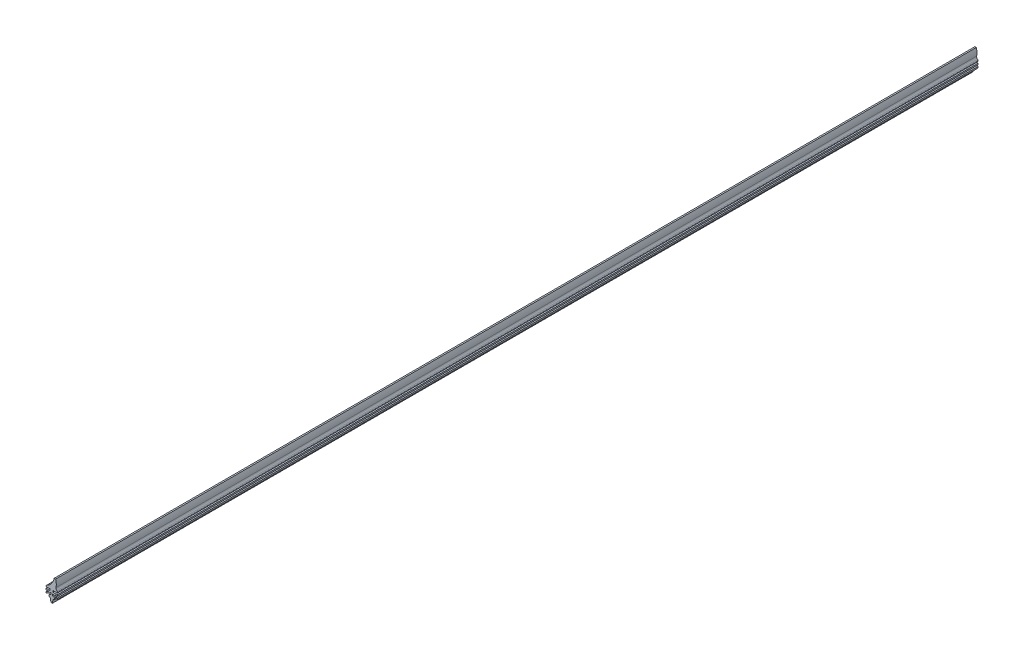
SolidWorks part; units mm, degrees
material "Caoutchouc"
ref_plane "Plan de face" through (0, 0, 0) normal (0, 0, 1) x (1, 0, 0)
ref_plane "Plan de dessus" through (0, 0, 0) normal (0, 1, 0) x (1, 0, 0)
ref_plane "Plan de droite" through (0, 0, 0) normal (1, 0, 0) x (0, 0, -1)
sketch "Esquisse1" plane through (0, 0, 0) normal (0, 0, 1) x (1, 0, 0)
  line L0 (0, 0) -> (0, -7.2441) construction
  line L1 (4, 0) -> (1, 0)
  line L2 (-8, 0) -> (-1, 0) construction
  line L3 (-4, 0) -> (-4, -1)
  line L4 (4, 0) -> (4, -1)
  line L5 (-4, -1) -> (-2.2647, -1)
  line L6 (4, -1) -> (2.2647, -1)
  line L7 (-2.2647, -1) -> (-4, -2)
  line L8 (2.2647, -1) -> (4, -2)
  line L9 (-4, -2) -> (-4, -3)
  line L10 (4, -2) -> (4, -3)
  line L11 (-4, -3) -> (-0.5, -0.9831)
  line L12 (4, -3) -> (0.5, -0.9831)
  line L13 (-0.5, -0.9831) -> (-0.5, -2.1372)
  line L14 (0.5, -0.9831) -> (0.5, -2.1372)
  line L15 (-0.5, -2.1372) -> (-2, -3.0016)
  line L16 (0.5, -2.1372) -> (2, -3.0016)
  line L17 (-2, -3.0016) -> (-2, -4.0016)
  line L18 (2, -3.0016) -> (2, -4.0016)
  line L19 (-2, -4.0016) -> (-1.8471, -4.0016)
  line L20 (2, -4.0016) -> (1.8471, -4.0016)
  line L21 (-0.8607, -4.8371) -> (-0.5, -7)
  line L22 (0.8607, -4.8371) -> (0.5, -7)
  line L23 (-0.5, -7) -> (0.5, -7)
  line L24 (1, 1) -> (8, 1) construction
  line L25 (0, 0) -> (0, 8.6585) construction
  line L26 (8, 1) -> (8, 0) construction
  line L27 (-8, 1) -> (-1, 1) construction
  line L28 (1.798, 9) -> (2.798, 9)
  line L29 (4, 1.5) -> (4, 1)
  line L30 (-4, 1.202) -> (-4, 1)
  line L31 (-8, 1) -> (-8, 0) construction
  line L32 (-1, 1) -> (-4, 1)
  line L33 (-1, 1) -> (-1, 0)
  line L34 (1, 0) -> (1, 1)
  line L35 (1, 1) -> (4, 1)
  line L36 (-1, 0) -> (-4, 0)
  arc A0 (0.8607, -4.8371) -> (1.8471, -4.0016) centre (1.8471, -5.0016) cw
  arc A1 (-0.8607, -4.8371) -> (-1.8471, -4.0016) centre (-1.8471, -5.0016) ccw
  arc A2 (-3.4545, 2.0928) -> (1.798, 9) centre (-8, 11) ccw
  arc A3 (3.035, 3.8221) -> (3.6, 2.3) centre (4.5, 3.5) ccw
  arc A4 (-4, 1.202) -> (-3.4545, 2.0928) centre (-3, 1.202) cw
  arc A5 (3.035, 3.8221) -> (2.798, 9) centre (-6.7317, 5.9694) ccw
  arc A6 (4, 1.5) -> (3.6, 2.3) centre (3, 1.5) ccw
  point P28 (0, -7)
  point P32 (1, -4.0016)
  point P35 (-1, -4.0016)
  dimension "D13" = 1
  dimension "D16" = 20
  dimension "D19" = 3
  dimension "D22" = 1
  dimension "D1" = 1
  dimension "D2" = 4
  dimension "D3" = 1
  dimension "D4" = 8
  dimension "D5" = 8
  dimension "D6" = 1
  dimension "D7" = 1
  dimension "D8" = 1
  dimension "D9" = 1
  dimension "D10" = 1
  dimension "D11" = 8
  dimension "D12" = 2
  dimension "D14" = 16
  dimension "D15" = 10
  dimension "D17" = 8
  dimension "D18" = 1
  dimension "D20" = 2.5
  dimension "D21" = 4.5
  dimension "D23" = 4
extrude "Extrusion1" add sketch "Esquisse1" against normal blind 650
